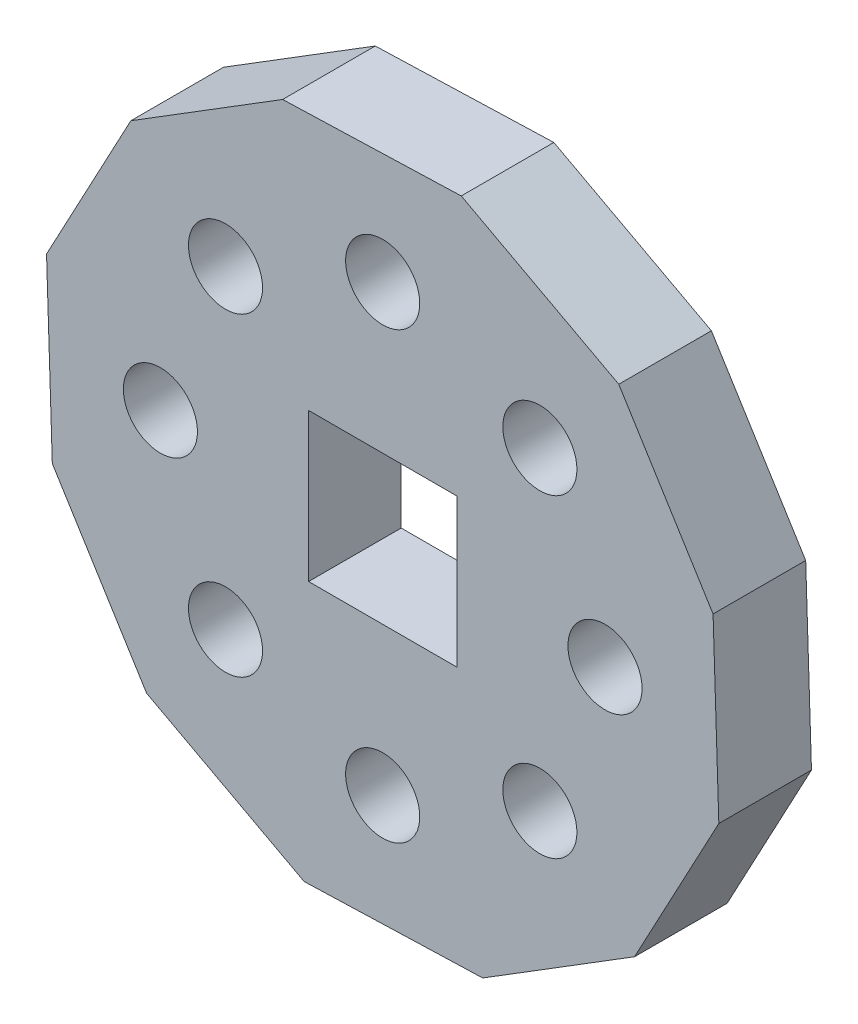
SolidWorks part; units mm, degrees
ref_plane "Front Plane" through (0, 0, 0) normal (0, 0, 1) x (1, 0, 0)
ref_plane "Top Plane" through (0, 0, 0) normal (0, 1, 0) x (1, 0, 0)
ref_plane "Right Plane" through (0, 0, 0) normal (1, 0, 0) x (0, 0, -1)
sketch "Sketch3" plane through (0, 0, 0) normal (0, 0, 1) x (1, 0, 0)
  line L1 (21.1996, 90.7311) -> (-27.0061, 89.1752)
  line L2 (-27.0061, 89.1752) -> (-67.9756, 63.725)
  line L3 (-67.9756, 63.725) -> (-90.7311, 21.1996)
  line L4 (-90.7311, 21.1996) -> (-89.1752, -27.0061)
  line L5 (-89.1752, -27.0061) -> (-63.725, -67.9756)
  line L6 (-63.725, -67.9756) -> (-21.1996, -90.7311)
  line L7 (-21.1996, -90.7311) -> (27.0061, -89.1752)
  line L8 (27.0061, -89.1752) -> (67.9756, -63.725)
  line L9 (67.9756, -63.725) -> (90.7311, -21.1996)
  line L10 (90.7311, -21.1996) -> (89.1752, 27.0061)
  line L11 (89.1752, 27.0061) -> (63.725, 67.9756)
  line L12 (63.725, 67.9756) -> (21.1996, 90.7311)
  line L13 (-20, -20) -> (20, -20)
  line L14 (-20, -20) -> (-20, 20)
  line L15 (-20, 20) -> (20, 20)
  line L16 (20, -20) -> (20, 20)
  line L17 (-20, -20) -> (20, 20) construction
  line L18 (-20, 20) -> (20, -20) construction
  circle A0 centre (0, 0) radius 90 construction
  circle A1 centre (0, 0) radius 60 construction
  circle A2 centre (0, 60) radius 10
  circle A3 centre (42.4264, 42.4264) radius 10
  circle A4 centre (60, 0) radius 10
  circle A5 centre (42.4264, -42.4264) radius 10
  circle A6 centre (0, -60) radius 10
  circle A7 centre (-42.4264, -42.4264) radius 10
  circle A8 centre (-60, 0) radius 10
  circle A9 centre (-42.4264, 42.4264) radius 10
  point P19 (2.9033, -89.9532)
  point P39 (0, 0)
  dimension "D4" = 8
  dimension "D1" = 40
  dimension "D2" = 40
  dimension "D3" = 180
extrude "Boss-Extrude1" add sketch "Sketch3" along normal blind 25
